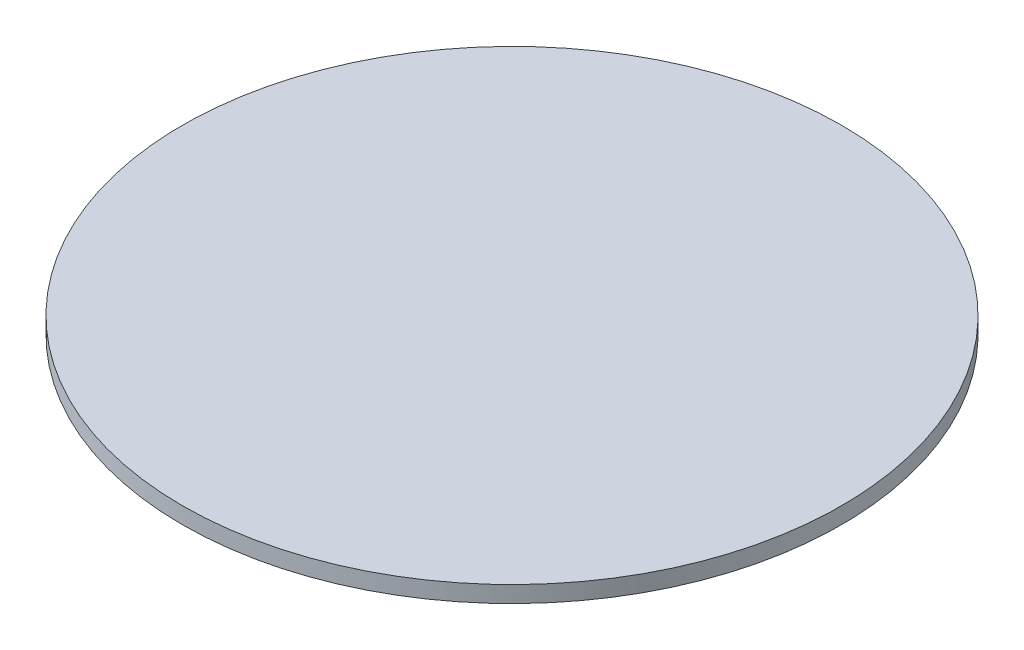
SolidWorks part; units mm, degrees
ref_plane "Front Plane" through (0, 0, 0) normal (0, 0, 1) x (1, 0, 0)
ref_plane "Top Plane" through (0, 0, 0) normal (0, 1, 0) x (1, 0, 0)
ref_plane "Right Plane" through (0, 0, 0) normal (1, 0, 0) x (0, 0, -1)
sketch "Sketch1" plane through (0, 0, 0) normal (0, 1, 0) x (1, 0, 0)
  circle A0 centre (0, 0) radius 100
  dimension "D1" = 200
extrude "Boss-Extrude1" add sketch "Sketch1" along normal blind 5
